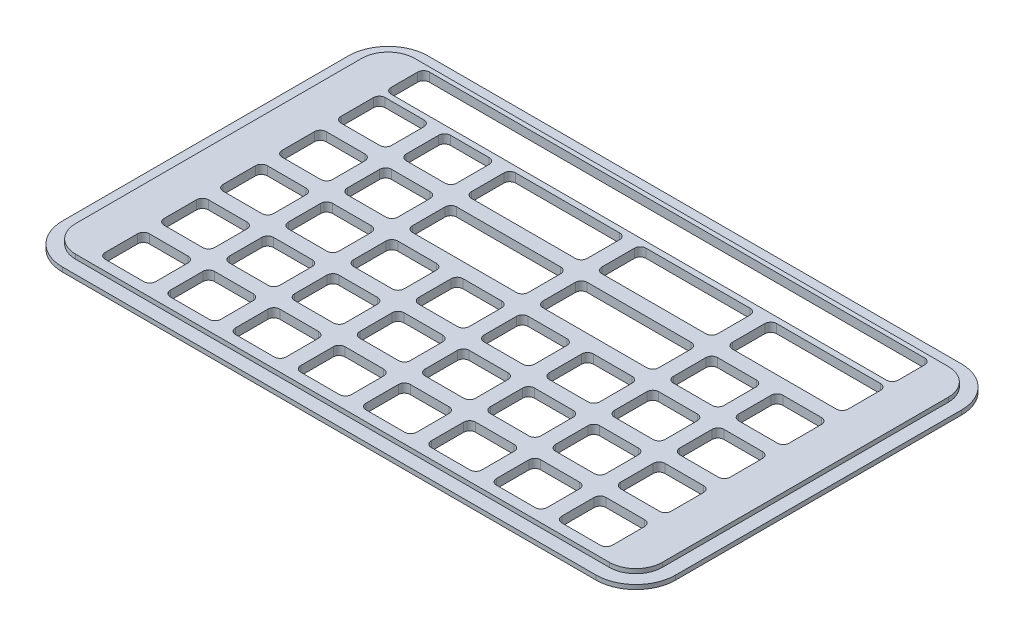
SolidWorks part; units mm, degrees
ref_plane "Front Plane" through (0, 0, 0) normal (0, 0, 1) x (1, 0, 0)
ref_plane "Top Plane" through (0, 0, 0) normal (0, 1, 0) x (1, 0, 0)
ref_plane "Right Plane" through (0, 0, 0) normal (1, 0, 0) x (0, 0, -1)
sketch "Sketch1" plane through (0, 0, 0) normal (0, 1, 0) x (1, 0, 0)
  line L1 (-104, -62) -> (104, -62)
  line L2 (-104, -62) -> (-104, 62)
  line L3 (-104, 62) -> (104, 62)
  line L4 (104, -62) -> (104, 62)
  line L5 (-104, -62) -> (104, 62) construction
  line L6 (-104, 62) -> (104, -62) construction
  point P0 (0, 0)
  dimension "D1" = 208
  dimension "D2" = 124
extrude "Outer Profile" add sketch "Sketch1" along normal blind 1.5
sketch "Sketch2" plane through (0, 1.5, 0) normal (0, 1, 0) x (1, 0, 0)
  line L1 (-99.5, -57.5) -> (99.5, -57.5)
  line L2 (-99.5, -57.5) -> (-99.5, 57.5)
  line L3 (-99.5, 57.5) -> (99.5, 57.5)
  line L4 (99.5, -57.5) -> (99.5, 57.5)
  line L5 (-99.5, -57.5) -> (99.5, 57.5) construction
  line L6 (-99.5, 57.5) -> (99.5, -57.5) construction
  point P0 (0, 0)
  dimension "D1" = 199
  dimension "D2" = 115
extrude "Inner Profile" add sketch "Sketch2" along normal blind 1.5
fillet "Fillet1" radius 9 4 edges at (99.5, 2.25, 57.5) (99.5, 2.25, -57.5) (-99.5, 2.25, -57.5) (-99.5, 2.25, 57.5)
fillet "Fillet2" radius 13.5 4 edges at (-104, 0.75, -62) (104, 0.75, -62) (104, 0.75, 62) (-104, 0.75, 62)
sketch "Sketch3" plane through (0, 3, 0) normal (0, 1, 0) x (1, 0, 0)
  line L1 (-86, -54) -> (86, -54) construction
  line L2 (-86, -54) -> (-86, 54) construction
  line L3 (-86, 54) -> (86, 54) construction
  line L4 (86, -54) -> (86, 54) construction
  line L5 (-86, -54) -> (86, 54) construction
  line L6 (-86, 54) -> (86, -54) construction
  point P0 (0, 0)
  dimension "D1" = 172
  dimension "D2" = 108
sketch "Sketch4" plane through (0, 3, 0) normal (0, 1, 0) x (1, 0, 0)
  line L0 (-86, -54) -> (-86, 54) construction
  line L1 (-86, 43) -> (86, 43)
  line L2 (-86, 43) -> (-86, 56)
  line L3 (-86, 56) -> (86, 56)
  line L4 (86, 43) -> (86, 56)
  line L10 (-86, 54) -> (86, 54) construction
  dimension "D1" = 2
  dimension "D2" = 11
  dimension "D3" = 172
extrude "Message Bar" cut sketch "Sketch4" against normal through all
sketch "Sketch5" plane through (0, 3, 0) normal (0, 1, 0) x (1, 0, 0)
  line L1 (-86, -54) -> (-68.875, -54)
  line L2 (-86, -54) -> (-86, -39)
  line L3 (-86, -39) -> (-68.875, -39)
  line L4 (-68.875, -54) -> (-68.875, -39)
  dimension "D1" = 17.125
  dimension "D2" = 15
extrude "Cutout" cut sketch "Sketch5" against normal through all
pattern_linear "Cutouts" count 8 spacing 22.125 along (1, 0, 0) count 5 spacing 20 along (0, 0, -1) of "Cutout"
sketch "Sketch6" plane through (0, 3, 0) normal (0, 1, 0) x (1, 0, 0)
  line L0 (24.625, 41) -> (24.625, 26) construction
  line L1 (-24.625, 41) -> (-19.625, 41)
  line L2 (-24.625, 41) -> (-24.625, 26)
  line L3 (-24.625, 26) -> (-19.625, 26)
  line L4 (-19.625, 41) -> (-19.625, 26)
  line L5 (19.625, 41) -> (24.625, 41)
  line L6 (19.625, 41) -> (19.625, 26)
  line L7 (19.625, 26) -> (24.625, 26)
  line L8 (24.625, 41) -> (24.625, 26)
  line L9 (2.5, 26) -> (19.625, 26) construction
  line L10 (63.875, 41) -> (68.875, 41)
  line L11 (63.875, 41) -> (63.875, 26)
  line L12 (63.875, 26) -> (68.875, 26)
  line L13 (68.875, 41) -> (68.875, 26)
  line L14 (-24.625, 21) -> (-19.625, 21)
  line L15 (-24.625, 21) -> (-24.625, 6)
  line L16 (-24.625, 6) -> (-19.625, 6)
  line L17 (-19.625, 21) -> (-19.625, 6)
  line L18 (19.625, 21) -> (24.625, 21)
  line L19 (19.625, 21) -> (19.625, 6)
  line L20 (19.625, 6) -> (24.625, 6)
  line L21 (24.625, 21) -> (24.625, 6)
extrude "Cut-Extrude3" cut sketch "Sketch6" against normal through all
fillet "Rads" radius 2 44 edges at (-63.875, 1.5, -1) (-63.875, 1.5, 19) (-41.75, 1.5, 39) (-19.625, 1.5, -1) (24.625, 1.5, 39) (46.75, 1.5, 39) (86, 1.5, -1) (86, 1.5, 39) (41.75, 1.5, -41) (41.75, 1.5, -26) (19.625, 1.5, 39) (19.625, 1.5, -1) (-2.5, 1.5, -41) (-2.5, 1.5, -26) (-2.5, 1.5, -1) (-24.625, 1.5, -1) (-46.75, 1.5, -21) (-68.875, 1.5, -1) (-68.875, 1.5, 34) (-46.75, 1.5, 14) (-46.75, 1.5, -6) (-24.625, 1.5, 14) (-24.625, 1.5, 54) (-2.5, 1.5, 14) (19.625, 1.5, 54) (41.75, 1.5, 54) (41.75, 1.5, 34) (86, 1.5, -6) (2.5, 1.5, -41) (68.875, 1.5, 14) (46.75, 1.5, -26) (46.75, 1.5, 34) (46.75, 1.5, 54) (24.625, 1.5, 34) (-19.625, 1.5, 34) (-19.625, 1.5, 14) (-41.75, 1.5, -26) (-41.75, 1.5, 14) (-63.875, 1.5, 54) (-63.875, 1.5, 34) (-63.875, 1.5, 14) (-86, 1.5, 34) (86, 1.5, -56) (-86, 1.5, -56)
chamfer "Chamfer" [suppressed] distance 0.5 angle 45
